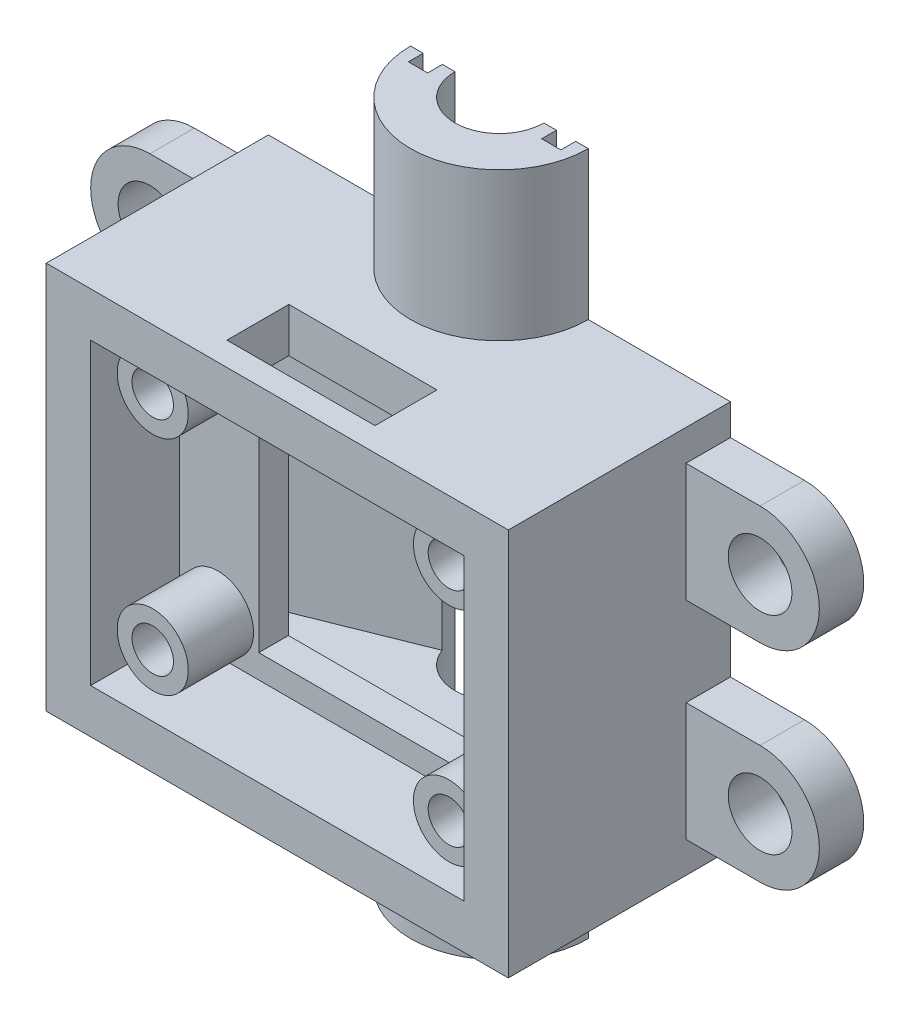
SolidWorks part; units mm, degrees
ref_plane "Front Plane" through (0, 0, 0) normal (0, 0, 1) x (1, 0, 0)
ref_plane "Top Plane" through (0, 0, 0) normal (0, 1, 0) x (1, 0, 0)
ref_plane "Right Plane" through (0, 0, 0) normal (1, 0, 0) x (0, 0, -1)
sketch "Sketch1" plane through (0, 0, 0) normal (0, 0, 1) x (1, 0, 0)
  line L1 (-15.6, -13.1) -> (15.6, -13.1)
  line L2 (-15.6, -13.1) -> (-15.6, 13.1)
  line L3 (-15.6, 13.1) -> (15.6, 13.1)
  line L4 (15.6, -13.1) -> (15.6, 13.1)
  line L5 (-15.6, -13.1) -> (15.6, 13.1) construction
  line L6 (-15.6, 13.1) -> (15.6, -13.1) construction
  point P0 (0, 0)
  dimension "D1" = 26.2
  dimension "D2" = 31.2
extrude "Boss-Extrude1" add sketch "Sketch1" along normal blind 15
shell "Shell2" thickness 3
sketch "Sketch3" plane through (0, 13.1, 0) normal (0, 1, 0) x (1, 0, 0)
  line L0 (15.6, 0) -> (-15.6, 0) construction
  line L1 (-6, 0) -> (-3, 0)
  line L2 (3, 0) -> (6, 0)
  arc A0 (-6, 0) -> (6, 0) centre (0, 0) ccw
  arc A1 (-3, 0) -> (3, 0) centre (0, 0) ccw
  dimension "D2" = 3
  dimension "D1" = 3
extrude "Boss-Extrude2" add sketch "Sketch3" along normal blind 10
ref_plane "Plane1" through (0, 0, 0) normal (0, 1, 0) x (1, 0, 0)
mirror "Mirror1" about plane through (0, 0, 0) normal (0, 1, 0) of "Boss-Extrude2"
sketch "Sketch4" plane through (0, 13.1, 0) normal (0, 1, 0) x (1, 0, 0)
  line L0 (3, 0) -> (-3, 0) construction
  line L1 (-3, 0) -> (3, 0)
  arc A0 (-3, 0) -> (3, 0) centre (0, 0) ccw
extrude "Cut-Extrude2" cut sketch "Sketch4" against normal through all
sketch "Sketch5" plane through (0, 13.1, 0) normal (0, 1, 0) x (1, 0, 0)
  line L1 (-5, -9.22) -> (5, -9.22)
  line L2 (-5, -9.22) -> (-5, -13.4)
  line L3 (-5, -13.4) -> (5, -13.4)
  line L4 (5, -9.22) -> (5, -13.4)
  line L5 (-5, -9.22) -> (5, -13.4) construction
  line L6 (-5, -13.4) -> (5, -9.22) construction
  line L9 (15.6, -15) -> (-15.6, -15) construction
  point P0 (0, -11.31)
  dimension "D1" = 10
  dimension "D3" = 4.18
  dimension "D4" = 1.6
sketch "Sketch8" plane through (0, 0, 0) normal (0, 0, -1) x (-1, 0, 0)
  line L0 (-15.6, 11) -> (-20.6, 11)
  line L1 (-15.6, -13.1) -> (-15.6, 13.1) construction
  line L2 (-15.6, 3) -> (-20.6, 3)
  line L3 (8.25, 0) -> (-8.25, 0) construction
  line L4 (-15.6, -3) -> (-20.6, -3)
  line L5 (-15.6, -11) -> (-20.6, -11)
  arc A0 (-20.6, 11) -> (-20.6, 3) centre (-20.6, 7) ccw
  circle A1 centre (-20.6, 7) radius 2.15
  circle A2 centre (-20.6, -7) radius 2.15
  arc A3 (-20.6, -11) -> (-20.6, -3) centre (-20.6, -7) cw
  line M9 (-15.6, 13.1) -> (-15.6, -13.1)
  dimension "D1" = 4.3
  dimension "D4" = 5
  dimension "D2" = 8
  dimension "D3" = 3
extrude "Boss-Extrude5" add sketch "Sketch8" against normal blind 3 contours L0 A0 L2 A1 M9 | A3 L5 L4 A2 M9
ref_plane "Plane3" through (0, 0, 0) normal (1, 0, 0) x (0, 0, -1)
sketch "Sketch7" plane through (0, 0, 0) normal (0, 0, -1) x (-1, 0, 0)
  line L0 (-4.5, -23.1) -> (-4.5, -11.6) construction
  line L1 (-6, -23.1) -> (-3, -23.1) construction
  line L3 (-4.5, -11.6) -> (-14.1, -11.6) construction
  line L4 (-14.1, -11.6) -> (-14.1, 11.6) construction
  line L5 (-14.1, 11.6) -> (-4.5, 11.6) construction
  line L6 (-4.5, 11.6) -> (-4.5, 23.1) construction
  line L7 (-6, 23.1) -> (-3, 23.1) construction
  line L8 (-15.6, -13.1) -> (-15.6, -11) construction
  line L9 (-15.6, 13.1) -> (-6, 13.1) construction
  line L10 (-6, -13.1) -> (-15.6, -13.1) construction
  line L11 (-3.85, -23.1) -> (-3.85, -10.95)
  line L12 (-3.85, -10.95) -> (-13.45, -10.95)
  line L13 (-13.45, -10.95) -> (-13.45, 10.95)
  line L14 (-13.45, 10.95) -> (-3.85, 10.95)
  line L15 (-3.85, 10.95) -> (-3.85, 23.1)
  line L16 (-5.15, -23.1) -> (-5.15, -12.25)
  line L17 (-5.15, -12.25) -> (-14.75, -12.25)
  line L18 (-14.75, -12.25) -> (-14.75, 12.25)
  line L19 (-14.75, 12.25) -> (-5.15, 12.25)
  line L20 (-5.15, 12.25) -> (-5.15, 23.1)
  line L21 (-5.15, 23.1) -> (-3.85, 23.1)
  line L22 (-5.15, -23.1) -> (-3.85, -23.1)
  dimension "D1" = 1.5
  dimension "D2" = 1.5
  dimension "D3" = 1.5
  dimension "D4" = 0.65
  dimension "D5" = 0.65
extrude "Cut-Extrude7" cut sketch "Sketch7" against normal blind 1 contours L18 L19 L20 L21 L15 L14 L13 L12 L11 L22 L16 L17
mirror "Mirror3" about plane through (0, 0, 0) normal (1, 0, 0) of "Cut-Extrude7", "Boss-Extrude5"
ref_plane "Plane2" through (0, 0, 0) normal (1, 0, 0) x (0, 0, -1)
sketch "Sketch14" plane through (0, 0, 12) normal (0, 0, -1) x (-1, 0, 0)
  line L1 (-12.6, 10.1) -> (12.6, 10.1)
  line L2 (-12.6, 10.1) -> (-12.6, -10.1)
  line L3 (-12.6, -10.1) -> (12.6, -10.1)
  line L4 (12.6, 10.1) -> (12.6, -10.1)
  line L5 (-12.6, 10.1) -> (12.6, -10.1) construction
  line L6 (-12.6, -10.1) -> (12.6, 10.1) construction
  point P0 (0, 0)
extrude "Cut-Extrude5" cut sketch "Sketch14" against normal through all
sketch "Sketch11" plane through (0, -10.1, 0) normal (0, 1, 0) x (1, 0, 0)
  line L0 (3, 0) -> (12.6, 0)
  line L1 (3, 0) -> (12.6, 0) construction
  line L2 (12.6, 0) -> (12.6, -5.003)
  line L3 (12.6, -15) -> (12.6, 0) construction
  line L4 (12.6, -5.003) -> (2.8013, -1.0736)
  line L5 (0, -8.25) -> (0, 8.25) construction
  line L6 (-12.6, -5.003) -> (-2.8013, -1.0736)
  line L7 (-12.6, 0) -> (-12.6, -5.003)
  line L8 (-3, 0) -> (-12.6, 0)
  arc A0 (-3, 0) -> (3, 0) centre (0, 0) ccw construction
  arc A1 (2.8013, -1.0736) -> (3, 0) centre (0, 0) ccw
  arc A2 (-2.8013, -1.0736) -> (-3, 0) centre (0, 0) cw
extrude "Boss-Extrude8" add sketch "Sketch11" along normal up to next
sketch "Sketch15" plane through (0, 0, 15) normal (0, 0, 1) x (1, 0, 0)
  line L1 (-15.6, 13.1) -> (15.6, 13.1)
  line L2 (-15.6, 13.1) -> (-15.6, -13.1)
  line L3 (-15.6, -13.1) -> (15.6, -13.1)
  line L4 (15.6, 13.1) -> (15.6, -13.1)
  line L5 (-15.6, 13.1) -> (15.6, -13.1) construction
  line L6 (-15.6, -13.1) -> (15.6, 13.1) construction
  line L7 (-7.25, 8.5) -> (7.25, 8.5)
  line L8 (-7.25, 8.5) -> (-7.25, -8.5)
  line L9 (-7.25, -8.5) -> (7.25, -8.5)
  line L10 (7.25, 8.5) -> (7.25, -8.5)
  line L11 (-7.25, 8.5) -> (7.25, -8.5) construction
  line L12 (-7.25, -8.5) -> (7.25, 8.5) construction
  point P0 (0, 0)
  point P7 (0, 0)
  point P12 (7.1136, -5.9736)
  point P13 (7.2472, -8.455)
  dimension "D1" = 17
  dimension "D2" = 14.5
extrude "Boss-Extrude9" add sketch "Sketch15" along normal blind 2 from offset 8 offset against normal yes
sketch "Sketch16" plane through (0, 0, 9) normal (0, 0, 1) x (1, 0, 0)
  line L1 (-12.6, 10.1) -> (-12.6, -10.1) construction
  line L5 (12.6, -10.1) -> (-12.6, -10.1) construction
  circle A0 centre (-10, 7.5) radius 2.4
  circle A1 centre (10, 7.5) radius 2.4
  circle A2 centre (-10, -7.5) radius 2.4
  circle A3 centre (10, -7.5) radius 2.4
  circle A4 centre (-10, 7.5) radius 1.4
  circle A5 centre (-10, -7.5) radius 1.4
  circle A6 centre (10, -7.5) radius 1.4
  circle A7 centre (10, 7.5) radius 1.4
  dimension "D1" = 2.8
  dimension "D2" = 2.8
  dimension "D3" = 2.8
  dimension "D4" = 2.8
  dimension "D5" = 1
  dimension "D6" = 1
  dimension "D7" = 1
  dimension "D8" = 1
  dimension "D9" = 20
  dimension "D10" = 2.6
  dimension "D11" = 15
  dimension "D12" = 2.6
extrude "Boss-Extrude10" add sketch "Sketch16" along normal blind 4.41
extrude "Cut-Extrude6" cut sketch "Sketch5" against normal up to next
equation "\"D2@Sketch7\"=\"D1@Sketch7\""
equation "\"D3@Sketch7\"=\"D1@Sketch7\""
equation "\"D2@Sketch16\"=\"D1@Sketch16\""
equation "\"D3@Sketch16\"=\"D1@Sketch16\""
equation "\"D4@Sketch16\"=\"D1@Sketch16\""
equation "\"D6@Sketch16\"=\"D5@Sketch16\""
equation "\"D7@Sketch16\"=\"D5@Sketch16\""
equation "\"D8@Sketch16\"=\"D5@Sketch16\""
